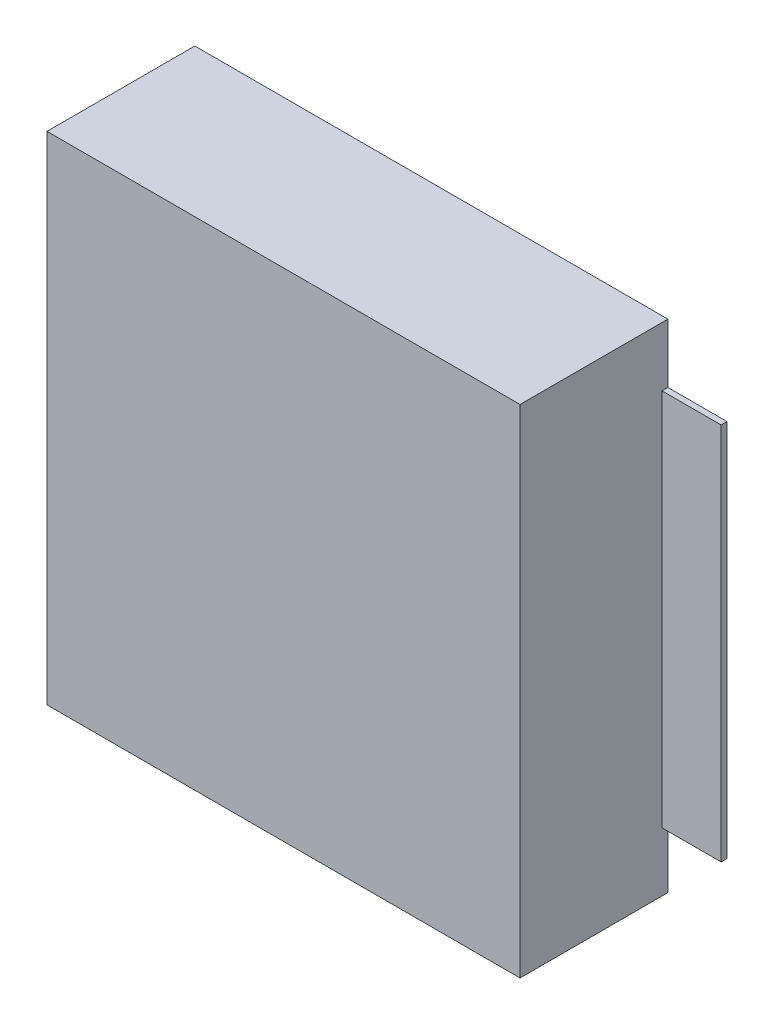
SolidWorks part; units mm, degrees
ref_plane "Alzado" through (0, 0, 0) normal (0, 0, 1) x (1, 0, 0)
ref_plane "Planta" through (0, 0, 0) normal (0, 1, 0) x (1, 0, 0)
ref_plane "Vista lateral" through (0, 0, 0) normal (1, 0, 0) x (0, 0, -1)
sketch "Croquis1" plane through (0, 0, 0) normal (0, 0, 1) x (1, 0, 0)
  line L1 (40, -42) -> (-40, -42)
  line L2 (40, -42) -> (40, 42)
  line L3 (40, 42) -> (-40, 42)
  line L4 (-40, -42) -> (-40, 42)
  line L5 (40, -42) -> (-40, 42) construction
  line L6 (40, 42) -> (-40, -42) construction
  point P0 (0, 0)
  dimension "D1" = 84
  dimension "D2" = 80
extrude "Saliente-Extruir1" add sketch "Croquis1" along normal blind 25
sketch "Croquis4" plane through (0, 0, 0) normal (0, 0, -1) x (-1, 0, 0)
  line L0 (-40, 42) -> (-50, 42)
  line L1 (-50, 42) -> (-50, -42)
  line L2 (-50, -42) -> (-40, -42)
  line L3 (-40, -42) -> (-40, 42)
  line L4 (40, 42) -> (50, 42)
  line L5 (50, 42) -> (50, -42)
  line L6 (50, -42) -> (40, -42)
  line L7 (40, -42) -> (40, 42)
  dimension "D1" = 10
  dimension "D2" = 10
extrude "Saliente-Extruir3" add sketch "Croquis4" against normal blind 1
sketch "Croquis8" plane through (0, 0, 1) normal (0, 0, 1) x (1, 0, 0)
  line L0 (40, 42) -> (40, 32)
  line L1 (40, -42) -> (40, 42) construction
  line L2 (40, 42) -> (50, 42)
  line L4 (50, 42) -> (50, 32)
  line L5 (50, 42) -> (50, -42) construction
  line L6 (50, 32) -> (40, 32)
  line L7 (40, -42) -> (40, -32)
  line L8 (40, -32) -> (50, -32)
  line L9 (50, -32) -> (50, -42)
  line L10 (50, -42) -> (40, -42)
  point P13 (0, 0)
  dimension "D1" = 10
  dimension "D2" = 10
sketch "Croquis11" plane through (0, 0, 1) normal (0, 0, 1) x (1, 0, 0)
  line L0 (-40, 42) -> (-40, -42) construction
  line L1 (-50, 42) -> (-40, 42)
  line L2 (-50, 42) -> (-50, 32)
  line L3 (-50, 32) -> (-40, 32)
  line L4 (-40, 42) -> (-40, 32)
  line L5 (-40, 42) -> (-40, -42) construction
  line L6 (-50, -42) -> (-40, -42)
  line L7 (-50, -42) -> (-50, -32)
  line L8 (-50, -32) -> (-40, -32)
  line L9 (-40, -42) -> (-40, -32)
  dimension "D1" = 10
  dimension "D2" = 10
extrude "Cortar-Extruir1" cut sketch "Croquis11" against normal blind 1
extrude "Cortar-Extruir2" cut sketch "Croquis8" against normal blind 1
